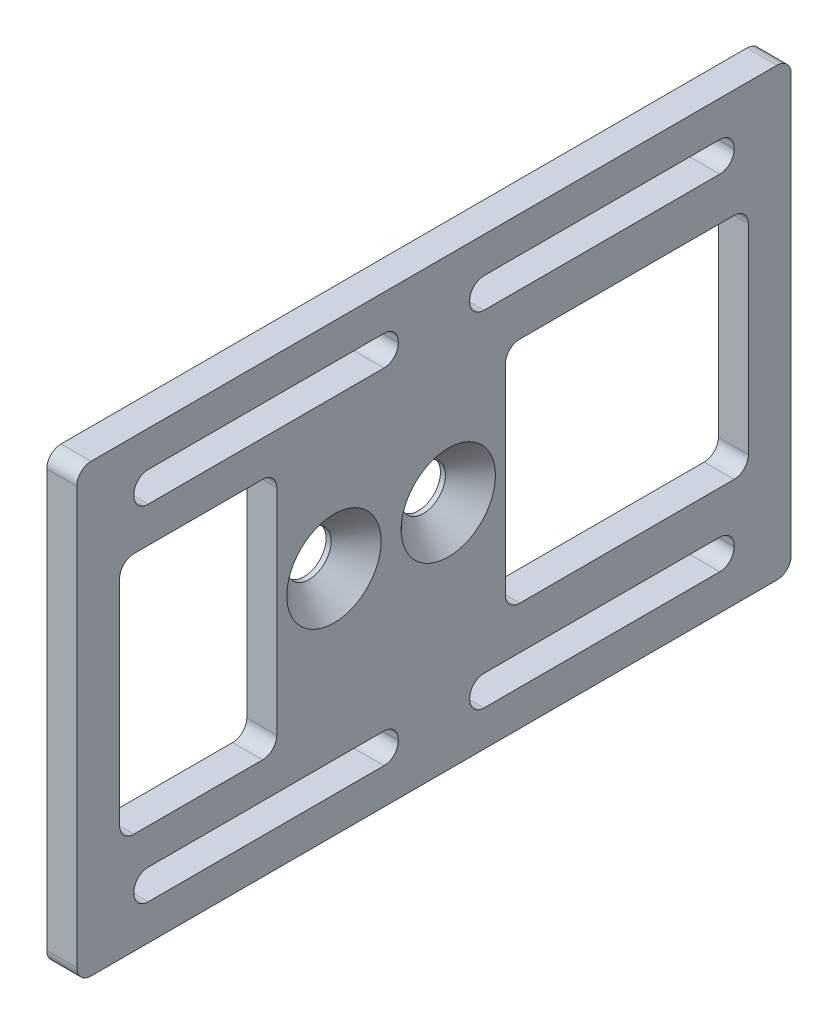
SolidWorks part; units mm, degrees
material "环氧树脂板"
ref_plane "前视基准面" through (0, 0, 0) normal (0, 0, 1) x (1, 0, 0)
ref_plane "上视基准面" through (0, 0, 0) normal (0, 1, 0) x (1, 0, 0)
ref_plane "右视基准面" through (0, 0, 0) normal (1, 0, 0) x (0, 0, -1)
sketch "草图1" plane through (0, 0, 0) normal (1, 0, 0) x (0, 0, -1)
  line L0 (7, -0.6) -> (7, 4.8493) construction
  line L1 (32, -16.2) -> (-18, -16.2)
  line L2 (32, -16.2) -> (32, 15)
  line L3 (32, 15) -> (-18, 15)
  line L4 (-18, -16.2) -> (-18, 15)
  line L5 (32, -16.2) -> (-18, 15) construction
  line L6 (32, 15) -> (-18, -16.2) construction
  line L7 (4.5, 10.4) -> (-14, 10.4)
  line L8 (4.5, 10.4) -> (4.5, 12.5)
  line L9 (4.5, 12.5) -> (-14, 12.5)
  line L10 (-14, 10.4) -> (-14, 12.5)
  line L11 (4.5, 10.4) -> (-14, 12.5) construction
  line L12 (4.5, 12.5) -> (-14, 10.4) construction
  line L13 (9.5, 12.5) -> (28, 12.5)
  line L14 (28, 10.4) -> (28, 12.5)
  line L15 (9.5, 10.4) -> (28, 10.4)
  line L16 (9.5, 10.4) -> (9.5, 12.5)
  line L17 (13.6573, -0.6) -> (-5.4908, -0.6) construction
  line L18 (9.5, -11.6) -> (9.5, -13.7)
  line L19 (9.5, -11.6) -> (28, -11.6)
  line L20 (28, -11.6) -> (28, -13.7)
  line L21 (9.5, -13.7) -> (28, -13.7)
  line L22 (4.5, -13.7) -> (-14, -13.7)
  line L23 (-14, -11.6) -> (-14, -13.7)
  line L24 (4.5, -11.6) -> (-14, -11.6)
  line L25 (4.5, -11.6) -> (4.5, -13.7)
  line L38 (4.5, -13.7) -> (4.5, -17.7) construction
  line L40 (29, -8.6) -> (12, -8.6)
  line L41 (29, -8.6) -> (29, 7.4)
  line L42 (29, 7.4) -> (12, 7.4)
  line L43 (12, -8.6) -> (12, 7.4)
  line L44 (29, -8.6) -> (12, 7.4) construction
  line L45 (29, 7.4) -> (12, -8.6) construction
  line L46 (-4, -9.1) -> (-15, -9.1)
  line L47 (-4, -9.1) -> (-4, 7.9)
  line L48 (-4, 7.9) -> (-15, 7.9)
  line L49 (-15, -9.1) -> (-15, 7.9)
  line L50 (-4, -9.1) -> (-15, 7.9) construction
  line L51 (-4, 7.9) -> (-15, -9.1) construction
  circle A0 centre (0, 0) radius 1.55
  circle A1 centre (8, 0) radius 1.55
  point P5 (-4.75, 11.45)
  point P6 (7, -0.6)
  point P31 (20.5, -0.6)
  point P46 (-9.5, -0.6)
  dimension "D2" = 3.1
  dimension "D1" = 8
  dimension "D3" = 18
  dimension "D4" = 15
  dimension "D5" = 50
  dimension "D6" = 4
  dimension "D7" = 5
  dimension "D8" = 2.1
  dimension "D9" = 2.5
  dimension "D10" = 22
  dimension "D14" = 4
  dimension "D15" = 3
  dimension "D16" = 3
  dimension "D17" = 3
  dimension "D18" = 2.5
  dimension "D19" = 2.5
  dimension "D20" = 4
  dimension "D11" = 2.5
extrude "凸台-拉伸1" add sketch "草图1" along normal blind 2.1
hole_wizard "打孔尺寸(%根据十字)槽沉头木螺钉的类型1" positions "3D草图1" profile "草图2" countersink size "M3" standard "GB" end condition through all
sketch3d "3D草图1"
  line L0 (2.1, 0, 0) -> (0, 0, 0) construction
  line L1 (2.1, 0, -8) -> (0, 0, -8) construction
  point P0 (2.1, 0, 0)
  point P4 (2.1, 0, -8)
sketch "草图2" plane through (2.1, 0, 0) normal (0, 1, 0) x (0, 0, -1)
  line L0 (0, 0) -> (0, 2.1)
  line L1 (0, 2.1) -> (1.55, 2.1)
  line L2 (1.55, 2.1) -> (1.55, 1.75)
  line L3 (1.55, 1.75) -> (3.3, 0)
  line L5 (3.3, 0) -> (0, 0)
  line L6 (-1.55, 1.75) -> (-3.3, 0) construction
  line L11 (0, -6.35) -> (0, 107.95) construction
  dimension "通孔孔直径" = 3.1
  dimension "通孔孔深度" = 2.1
  dimension "近端锥形沉头孔直径" = 6.6
  dimension "近端锥形沉头孔角度" = 90
fillet "圆角1" radius 1 28 edges at (1.05, -9.1, 4) (1.05, 7.9, 4) (1.05, 7.9, 15) (1.05, -9.1, 15) (1.05, -8.6, -29) (1.05, 7.4, -29) (1.05, 7.4, -12) (1.05, -8.6, -12) (1.05, -11.6, 14) (1.05, -13.7, 14) (1.05, -13.7, -4.5) (1.05, -11.6, -4.5) (1.05, -13.7, -9.5) (1.05, -13.7, -28) (1.05, -11.6, -28) (1.05, -11.6, -9.5) (1.05, 10.4, -28) (1.05, 12.5, -28) (1.05, 12.5, -9.5) (1.05, 10.4, -9.5) (1.05, 10.4, -4.5) (1.05, 12.5, -4.5) (1.05, 12.5, 14) (1.05, 10.4, 14) (1.05, 15, 18) (1.05, 15, -32) (1.05, -16.2, -32) (1.05, -16.2, 18)
